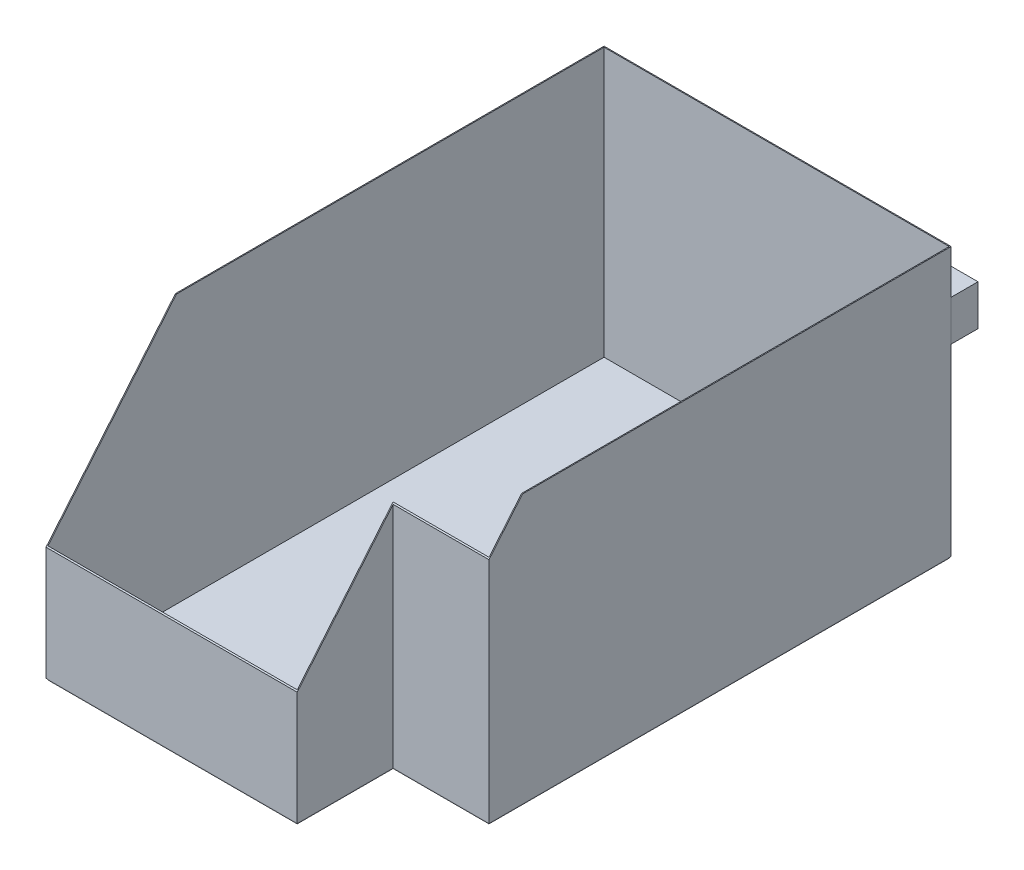
SolidWorks part; units mm, degrees
ref_plane "Front Plane" through (0, 0, 0) normal (0, 0, 1) x (1, 0, 0)
ref_plane "Top Plane" through (0, 0, 0) normal (0, 1, 0) x (1, 0, 0)
ref_plane "Right Plane" through (0, 0, 0) normal (1, 0, 0) x (0, 0, -1)
sketch "Sketch1" plane through (0, 0, 0) normal (0, 1, 0) x (1, 0, 0)
  line L1 (-82.1514, 217.8263) -> (277.8486, 217.8263)
  line L2 (-82.1514, 217.8263) -> (-82.1514, -362.1737)
  line L3 (-82.1514, -362.1737) -> (177.8486, -362.1737)
  line L4 (277.8486, 217.8263) -> (277.8486, -262.1737)
  line L6 (277.8486, -262.1737) -> (177.8486, -262.1737)
  line L7 (177.8486, -262.1737) -> (177.8486, -362.1737)
  dimension "D1" = 580
  dimension "D2" = 360
  dimension "D5" = 100
  dimension "D6" = 100
extrude "Boss-Extrude1" add sketch "Sketch1" along normal blind 1.5
sketch "Sketch2" plane through (0, 1.5, 0) normal (0, 1, 0) x (1, 0, 0)
  line L18 (-82.1514, 217.8263) -> (-82.1514, -362.1737)
  line L29 (-82.1514, -362.1737) -> (177.8486, -362.1737)
  line L30 (177.8486, -362.1737) -> (177.8486, -262.1737)
  line L31 (177.8486, -262.1737) -> (277.8486, -262.1737)
  line L32 (277.8486, -262.1737) -> (277.8486, 217.8263)
  line L33 (277.8486, 217.8263) -> (-82.1514, 217.8263)
  line L34 (-82.1514, 217.8263) -> (-82.1514, -362.1737)
  line L37 (-82.1514, -362.1737) -> (177.8486, -362.1737)
  line L38 (177.8486, -362.1737) -> (177.8486, -262.1737)
  line L39 (177.8486, -262.1737) -> (277.8486, -262.1737)
  line L40 (277.8486, -262.1737) -> (277.8486, 217.8263)
  line L41 (277.8486, 217.8263) -> (-82.1514, 217.8263)
  line L54 (-83.1514, -363.1737) -> (178.8486, -363.1737)
  line L55 (178.8486, -363.1737) -> (178.8486, -263.1737)
  line L56 (178.8486, -263.1737) -> (278.8486, -263.1737)
  line L57 (278.8486, -263.1737) -> (278.8486, 218.8263)
  line L58 (278.8486, 218.8263) -> (-83.1514, 218.8263)
  line L59 (-83.1514, 218.8263) -> (-83.1514, -363.1737)
  dimension "D1" = 0
  dimension "D2" = 1
extrude "Boss-Extrude2" add sketch "Sketch2" along normal blind 280
sketch "Sketch3" plane through (-82.1514, 0, 0) normal (-1, 0, 0) x (0, 0, 1)
  line L1 (-218.8263, 281.5) -> (363.1737, 281.5) construction
  line L4 (363.1737, 119.9205) -> (228.1952, 281.5)
  line L5 (228.1952, 281.5) -> (363.1737, 281.5)
  line L7 (363.1737, 281.5) -> (363.1737, 119.9205)
  line L8 (363.1737, 281.5) -> (363.1737, 1.5) construction
sketch "Sketch4" plane through (0, 0, -217.8263) normal (0, 0, -1) x (-1, 0, 0)
  line L0 (-277.8486, 1.5) -> (-277.8486, 0) construction
  line L1 (-277.8486, 234.6761) -> (82.1514, 234.6761)
  line L2 (-277.8486, 234.6761) -> (-277.8486, 192.2905)
  line L3 (-277.8486, 192.2905) -> (82.1514, 192.2905)
  line L4 (82.1514, 234.6761) -> (82.1514, 192.2905)
  line L5 (82.1514, 1.5) -> (82.1514, 0) construction
extrude "Boss-Extrude3" add sketch "Sketch4" along normal blind 30
extrude "Cut-Extrude1" cut sketch "Sketch3" against normal through all both and the other way through all
